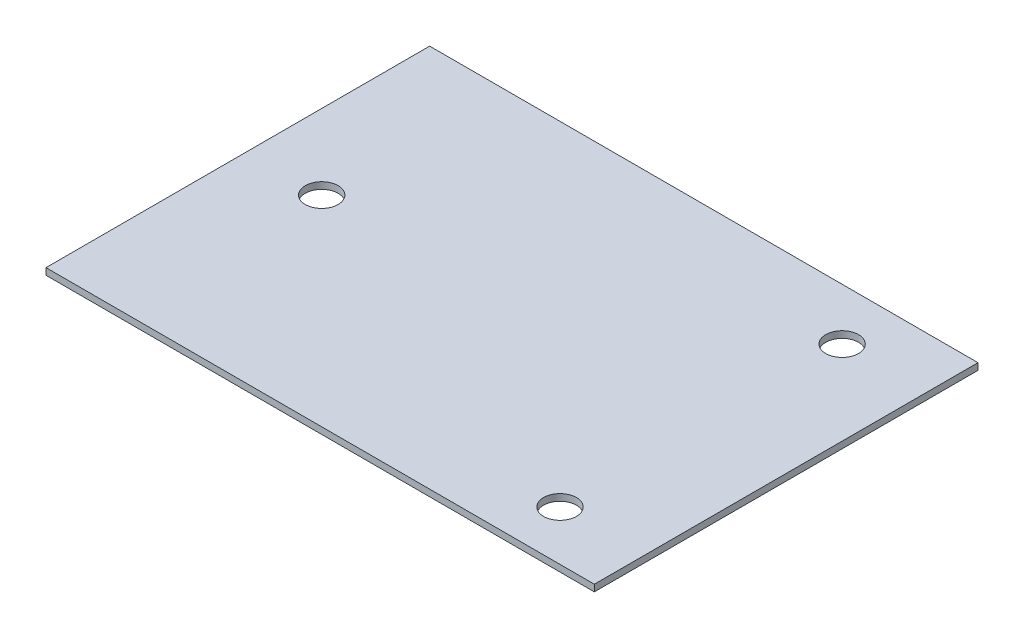
SolidWorks part; units mm, degrees
ref_plane "Front Plane" through (0, 0, 0) normal (0, 0, 1) x (1, 0, 0)
ref_plane "Top Plane" through (0, 0, 0) normal (0, 1, 0) x (1, 0, 0)
ref_plane "Right Plane" through (0, 0, 0) normal (1, 0, 0) x (0, 0, -1)
sketch "Sketch1" plane through (0, 0, 0) normal (0, 1, 0) x (1, 0, 0)
  line L5 (-27.4288, -6.6438) -> (-27.4288, 29.2222)
  line L8 (26.0865, -6.6438) -> (26.0865, 28.3562)
  line L10 (-27.4288, 29.2222) -> (-27.4288, 29.551)
  line L11 (-27.4288, 29.551) -> (26.0865, 29.551)
  line L12 (26.0865, 29.551) -> (26.0865, 28.3562)
  line L14 (-27.4288, -6.6438) -> (26.0865, -6.6438)
  line L15 (-27.4288, -6.6438) -> (-27.4288, -7.8938)
  line L16 (-27.4288, -7.8938) -> (26.0865, -7.8938)
  line L17 (26.0865, -6.6438) -> (26.0865, -7.8938)
  dimension "D1" = 1.25
extrude "Boss-Extrude1" add sketch "Sketch1" along normal blind 0.65 contours L5 L14 L8 L12 L11 L10 | L17 L14 L15 L16
sketch "Sketch2" plane through (0, 0, 0) normal (0, -1, 0) x (1, 0, 0)
  circle A0 centre (-20.1065, -11.6912) radius 1.6
  circle A1 centre (17.8825, 3.0408) radius 1.6
  circle A2 centre (17.8825, -24.4938) radius 1.6
extrude "Cut-Extrude1" cut sketch "Sketch2" against normal through all contours A0 | A2 | A1
